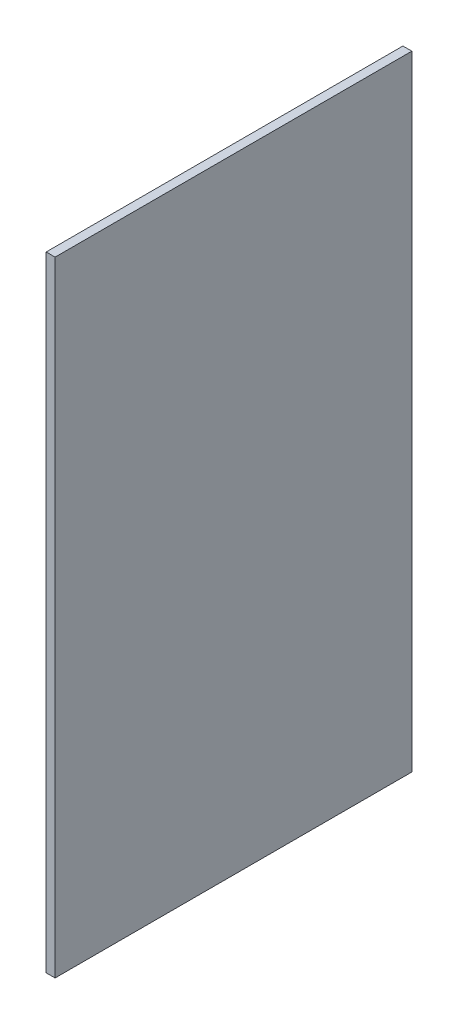
SolidWorks part; units mm, degrees
ref_plane "Front Plane" through (0, 0, 0) normal (0, 0, 1) x (1, 0, 0)
ref_plane "Top Plane" through (0, 0, 0) normal (0, 1, 0) x (1, 0, 0)
ref_plane "Right Plane" through (0, 0, 0) normal (1, 0, 0) x (0, 0, -1)
sketch "Sketch1" plane through (0, 0, 0) normal (1, 0, 0) x (0, 0, -1)
  line L1 (-36.6871, -32.1706) -> (-76.6871, -32.1706)
  line L2 (-36.6871, -32.1706) -> (-36.6871, 37.8294)
  line L3 (-36.6871, 37.8294) -> (-76.6871, 37.8294)
  line L4 (-76.6871, -32.1706) -> (-76.6871, 37.8294)
  dimension "Fin Heigth" = 70
  dimension "Fin Length" = 40
extrude "Boss-Extrude1" add sketch "Sketch1" along normal blind 1
